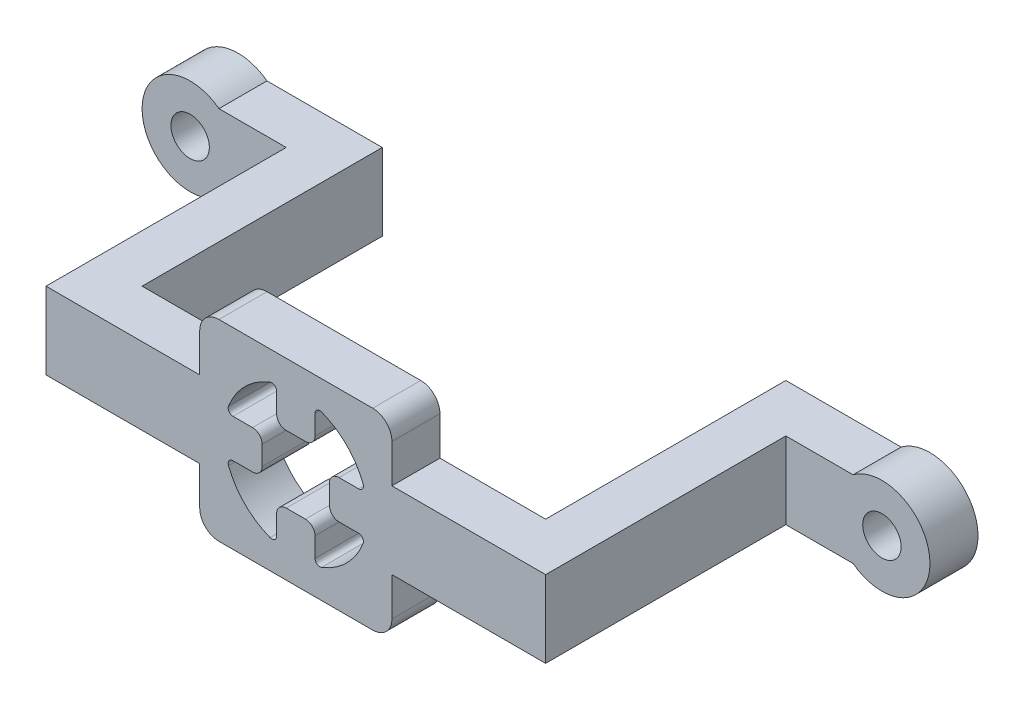
SolidWorks part; units mm, degrees
ref_plane "前视基准面" through (0, 0, 0) normal (0, 0, 1) x (1, 0, 0)
ref_plane "上视基准面" through (0, 0, 0) normal (0, 1, 0) x (1, 0, 0)
ref_plane "右视基准面" through (0, 0, 0) normal (1, 0, 0) x (0, 0, -1)
other "Configuration Table"
sketch "草图1" plane through (0, 0, 0) normal (0, 0, 1) x (1, 0, 0)
  circle A0 centre (0, 0) radius 5
  dimension "D1" = 10
extrude "凸台-拉伸1" add sketch "草图1" along normal blind 5
sketch "草图3" plane through (0, 0, 0) normal (1, 0, 0) x (0, 0, -1)
  line L0 (0, -5) -> (0, 5) construction
  line L1 (0, 4) -> (-5, 4)
  line L2 (0, 4) -> (0, -4)
  line L3 (0, -4) -> (-5, -4)
  line L4 (-5, 4) -> (-5, -4)
  line L5 (-5, 0) -> (0, 0) construction
  dimension "D1" = 5
  dimension "D2" = 8
  dimension "D3" = 4
extrude "凸台-拉伸2" add sketch "草图3" along normal blind 15
sketch "草图2" plane through (0, 0, 5) normal (0, 0, 1) x (1, 0, 0)
  circle A0 centre (0, 0) radius 2
  dimension "D1" = 4
extrude "切除-拉伸1" cut sketch "草图2" against normal blind 30
sketch "草图6" plane through (0, 0, 5) normal (0, 0, 1) x (1, 0, 0)
  line L0 (15, -4) -> (3, -4) construction
  line L1 (15, 4) -> (10, 4)
  line L2 (15, 4) -> (15, -4)
  line L3 (15, -4) -> (10, -4)
  line L4 (10, 4) -> (10, -4)
  dimension "D1" = 5
extrude "凸台-拉伸4" add sketch "草图6" along normal blind 25
sketch "草图7" plane through (15, 0, 0) normal (1, 0, 0) x (0, 0, -1)
  line L0 (-30, -4) -> (0, -4) construction
  line L1 (-30, 4) -> (-25, 4)
  line L2 (-30, 4) -> (-30, -4)
  line L3 (-30, -4) -> (-25, -4)
  line L4 (-25, 4) -> (-25, -4)
  dimension "D1" = 5
extrude "凸台-拉伸5" add sketch "草图7" along normal blind 21
mirror "镜向2" about plane through (36, 0, 0) normal (1, 0, 0) of bodies 123
sketch "草图8" plane through (0, 0, 30) normal (0, 0, 1) x (1, 0, 0)
  line L0 (36, 4) -> (36, -4) construction
  line L1 (62, 4) -> (10, 4) construction
  line L2 (10, -4) -> (62, -4) construction
  line L3 (36, 0) -> (40.108, 0) construction
  line L5 (26, 10) -> (46, 10)
  line L6 (26, 10) -> (26, -10)
  line L7 (26, -10) -> (46, -10)
  line L8 (46, 10) -> (46, -10)
  dimension "D1" = 20
  dimension "D2" = 20
  dimension "D3" = 10
  dimension "D4" = 10
extrude "凸台-拉伸6" add sketch "草图8" against normal up to surface (5 mm away) up to face at (36, 0, 25)
fillet "圆角2" radius 2 4 edges at (46, -10, 27.5) (26, -10, 27.5) (26, 10, 27.5) (46, 10, 27.5)
sketch "草图9" plane through (0, 0, 30) normal (0, 0, 1) x (1, 0, 0)
  line L0 (36, 10) -> (36, -10) construction
  line L1 (44, 10) -> (28, 10) construction
  line L2 (28, -10) -> (44, -10) construction
  circle A0 centre (36, 0) radius 7.5
  dimension "D1" = 15
extrude "切除-拉伸3" cut sketch "草图9" against normal up to surface (5 mm away) up to face at (36, 0, 25)
sketch "草图10" plane through (0, 0, 30) normal (0, 0, 1) x (1, 0, 0)
  line L0 (36, 7.5) -> (36, -7.5) construction
  line L1 (28.5, 0) -> (43.5, 0) construction
  line L2 (36, 7.5) -> (43.5, 7.5) construction
  line L3 (43.5, 7.5) -> (43.5, -7.5) construction
  line L4 (43.5, -7.5) -> (28.5, -7.5) construction
  line L5 (28.5, -7.5) -> (28.5, 7.5) construction
  line L6 (28.5, 7.5) -> (36, 7.5) construction
  line L8 (34, 7.5) -> (38, 7.5)
  line L9 (34, 7.5) -> (34, 3.5)
  line L10 (34, 3.5) -> (38, 3.5)
  line L11 (38, 7.5) -> (38, 3.5)
  line L12 (43.5, 2) -> (39.5, 2)
  line L13 (43.5, 2) -> (43.5, -2)
  line L14 (43.5, -2) -> (39.5, -2)
  line L15 (39.5, 2) -> (39.5, -2)
  line L16 (34, -7.5) -> (38, -7.5)
  line L17 (34, -7.5) -> (34, -3.5)
  line L18 (34, -3.5) -> (38, -3.5)
  line L19 (38, -7.5) -> (38, -3.5)
  line L20 (28.5, 2) -> (32.5, 2)
  line L21 (28.5, 2) -> (28.5, -2)
  line L22 (28.5, -2) -> (32.5, -2)
  line L23 (32.5, 2) -> (32.5, -2)
  circle A0 centre (36, 0) radius 7.5 construction
  dimension "D1" = 4
  dimension "D2" = 4
  dimension "D3" = 2
  dimension "D4" = 4
  dimension "D5" = 4
  dimension "D6" = 4
  dimension "D7" = 4
  dimension "D8" = 2
  dimension "D9" = 4
  dimension "D10" = 2
  dimension "D11" = 4
  dimension "D12" = 2
extrude "凸台-拉伸7" add sketch "草图10" against normal up to surface (5 mm away) up to face at (43.5, 0, 25)
fillet "圆角3" radius 1 8 edges at (39.5, -2, 27.5) (39.5, 2, 27.5) (38, 3.5, 27.5) (38, -3.5, 27.5) (34, -3.5, 27.5) (34, 3.5, 27.5) (32.5, -2, 27.5) (32.5, 2, 27.5)
fillet "圆角4" radius 0.5 8 edges at (43.2284, 2, 27.5) (38, 7.2284, 27.5) (43.2284, -2, 27.5) (38, -7.2284, 27.5) (34, -7.2284, 27.5) (28.7716, -2, 27.5) (28.7716, 2, 27.5) (34, 7.2284, 27.5)
